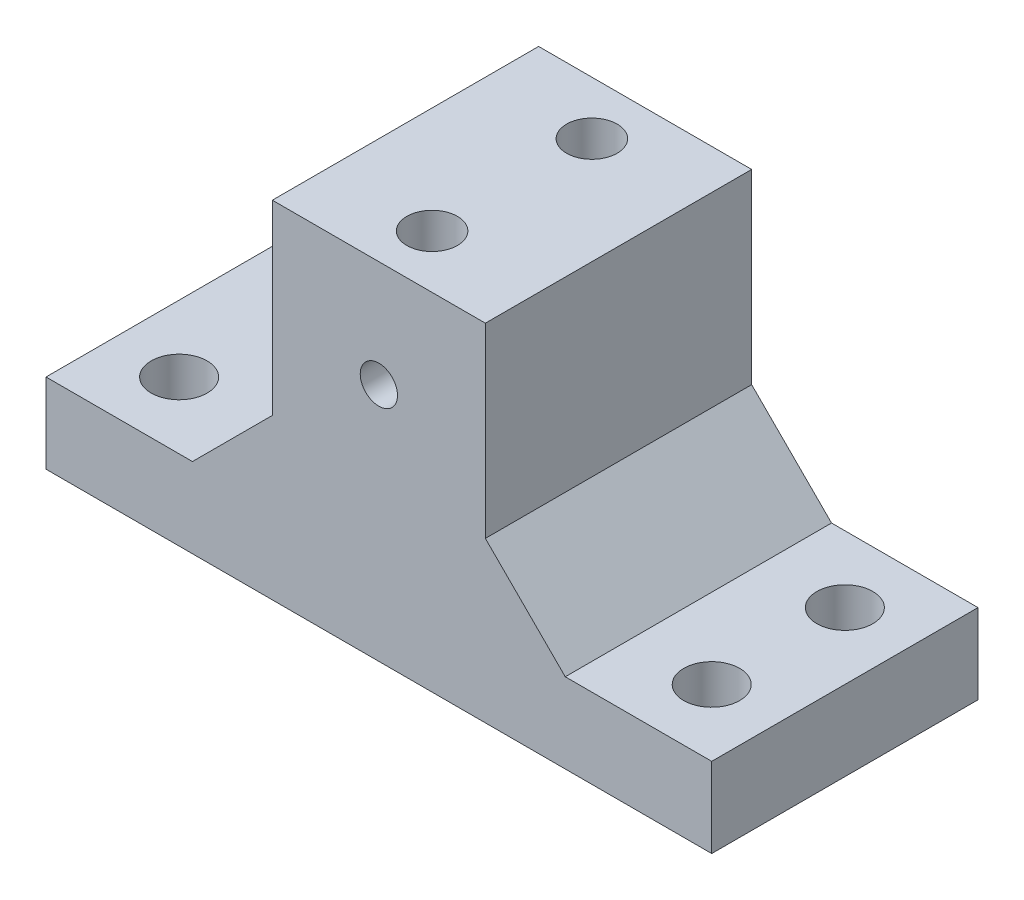
SolidWorks part; units mm, degrees
ref_plane "Front Plane" through (0, 0, 0) normal (0, 0, 1) x (1, 0, 0)
ref_plane "Top Plane" through (0, 0, 0) normal (0, 1, 0) x (1, 0, 0)
ref_plane "Right Plane" through (0, 0, 0) normal (1, 0, 0) x (0, 0, -1)
sketch "Sketch1" plane through (0, 0, 0) normal (0, 1, 0) x (1, 0, 0)
  line L1 (-12.5, -5) -> (12.5, -5)
  line L2 (-12.5, -5) -> (-12.5, 5)
  line L3 (-12.5, 5) -> (12.5, 5)
  line L4 (12.5, -5) -> (12.5, 5)
  line L5 (-12.5, -5) -> (12.5, 5) construction
  line L6 (-12.5, 5) -> (12.5, -5) construction
  line L7 (-10, -2.5) -> (10, -2.5) construction
  line L8 (-10, -2.5) -> (-10, 2.5) construction
  line L9 (-10, 2.5) -> (10, 2.5) construction
  line L10 (10, -2.5) -> (10, 2.5) construction
  line L11 (-10, -2.5) -> (10, 2.5) construction
  line L12 (-10, 2.5) -> (10, -2.5) construction
  circle A0 centre (-10, 2.5) radius 1.05
  circle A1 centre (-10, -2.5) radius 1.05
  circle A2 centre (10, 2.5) radius 1.05
  circle A3 centre (10, -2.5) radius 1.05
  point P0 (0, 0)
  point P6 (0, 0)
  dimension "D3" = 5
  dimension "D5" = 2.1
  dimension "D1" = 25
  dimension "D2" = 10
  dimension "D4" = 20
extrude "Boss-Extrude1" add sketch "Sketch1" along normal blind 3
sketch "Sketch3" plane through (0, 0, -5) normal (0, 0, -1) x (-1, 0, 0)
  line L0 (-12.5, 0) -> (12.5, 0) construction
  line L1 (-4, 0) -> (4, 0)
  line L2 (-4, 0) -> (-4, 13)
  line L3 (-4, 13) -> (4, 13)
  line L4 (4, 0) -> (4, 13)
  line L5 (0, 13) -> (0, 0) construction
  dimension "D1" = 13
  dimension "D2" = 8
extrude "Boss-Extrude2" add sketch "Sketch3" against normal up to surface (10 mm away) up to face at (0, 1.5, 5)
sketch "Sketch4" plane through (0, 0, -5) normal (0, 0, -1) x (-1, 0, 0)
  line L0 (0, 0) -> (0, 9) construction
  circle A0 centre (0, 9) radius 0.7
  dimension "D2" = 1.4
  dimension "D1" = 9
extrude "Cut-Extrude1" cut sketch "Sketch4" against normal through all
sketch "Sketch5" plane through (0, 13, 0) normal (0, 1, 0) x (1, 0, 0)
  line L0 (0, 3) -> (0, -3) construction
  line L1 (-4, 5) -> (4, 5) construction
  circle A0 centre (0, 3) radius 0.95
  circle A2 centre (0, -3) radius 0.95
  dimension "D1" = 1.9
  dimension "D2" = 2
extrude "Cut-Extrude2" cut sketch "Sketch5" against normal blind 3.5
chamfer "Chamfer1" distance 3 angle 45 2 edges at (-4, 3, 0) (4, 3, 0)
